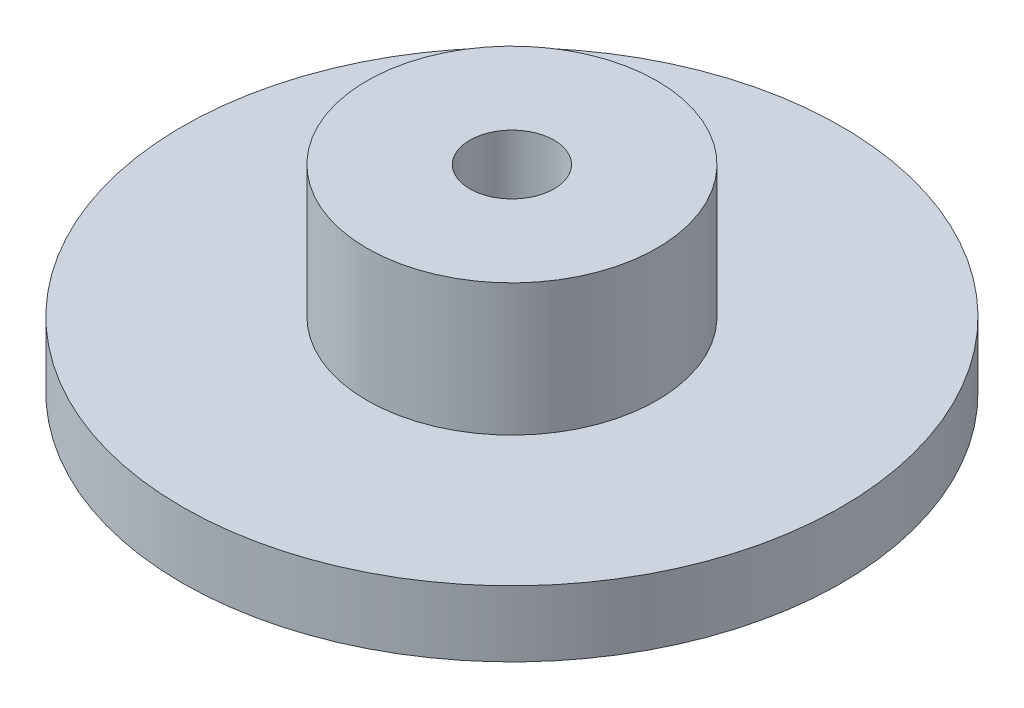
SolidWorks part; units mm, degrees
ref_plane "Front Plane" through (0, 0, 0) normal (0, 0, 1) x (1, 0, 0)
ref_plane "Top Plane" through (0, 0, 0) normal (0, 1, 0) x (1, 0, 0)
ref_plane "Right Plane" through (0, 0, 0) normal (1, 0, 0) x (0, 0, -1)
sketch "Sketch1" plane through (0, 0, 0) normal (0, 1, 0) x (1, 0, 0)
  circle A0 centre (0, 0) radius 12.5
  dimension "D1" = 25
extrude "Boss-Extrude1" add sketch "Sketch1" along normal blind 2.5
sketch "Sketch2" plane through (0, 2.5, 0) normal (0, 1, 0) x (1, 0, 0)
  circle A0 centre (0, 0) radius 5.5
  dimension "D1" = 11
extrude "Boss-Extrude2" add sketch "Sketch2" along normal blind 5
hole_wizard "Hole1" positions "Sketch3" profile "Sketch5" legacy
sketch "Sketch3" plane through (0, 0, 0) normal (0, -1, 0) x (-1, 0, 0)
  point P0 (0, 0)
sketch "Sketch5" plane through (0, 0, 0) normal (1, 0, 0) x (0, 0, -1)
  line L0 (0, 0) -> (0, 100)
  line L1 (0, 100) -> (1.6, 100)
  line L2 (1.6, 100) -> (1.6, 3)
  line L3 (1.6, 3) -> (4, 3)
  line L4 (4, 3) -> (4, 0)
  line L5 (4, 0) -> (0, 0)
  line L6 (0, 110) -> (0, -10) construction
  dimension "Diameter" = 3.2
  dimension "Depth" = 100
  dimension "C-Bore Diameter" = 8
  dimension "C-Bore Depth" = 3
